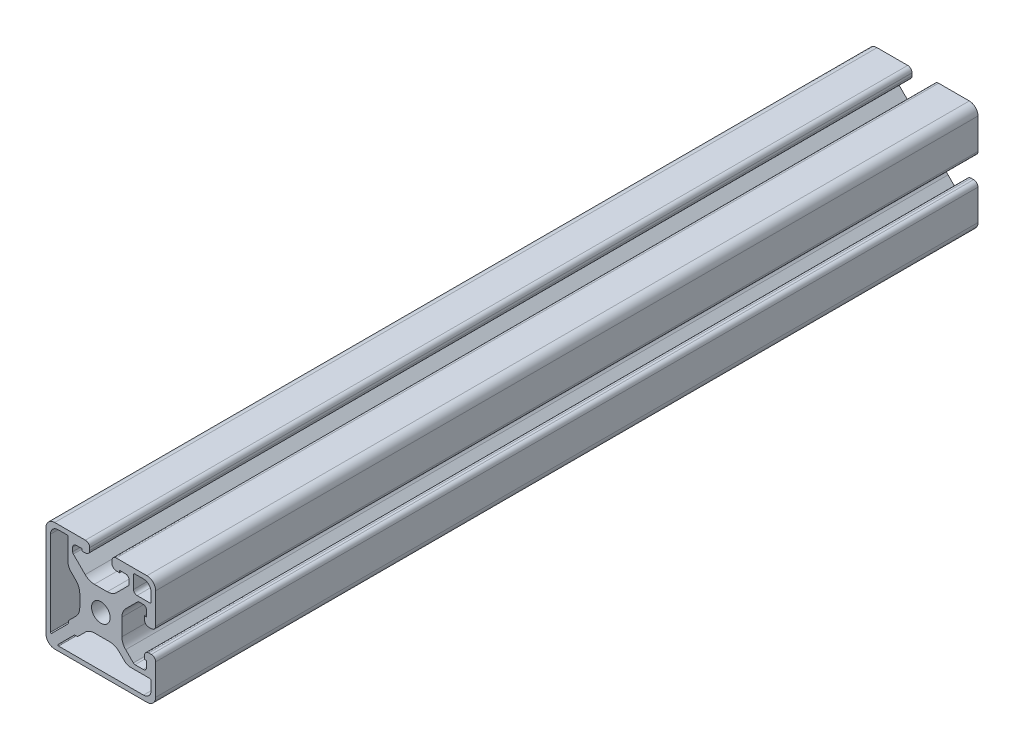
SolidWorks part; units mm, degrees
material "6105-T5 Aluminum"
ref_plane "Front Plane" through (0, 0, 0) normal (0, 0, 1) x (1, 0, 0)
ref_plane "Top Plane" through (0, 0, 0) normal (0, 1, 0) x (1, 0, 0)
ref_plane "Right Plane" through (0, 0, 0) normal (1, 0, 0) x (0, 0, -1)
sketch "Sketch1" plane through (0, 0, 0) normal (0, 0, 1) x (1, 0, 0)
  line L0 (20.9471, 20.9471) -> (-21.7247, -21.7247) construction
  line L1 (-28.5091, 0) -> (25.9724, 0) construction
  line L2 (2.356, 7.7) -> (-2.356, 7.7)
  line L3 (-2.2915, -7.67) -> (3.3048, -7.67)
  line L26 (-9.0762, -5.7416) -> (-11.6227, -8.288)
  line L27 (-7.685, 2.23) -> (-7.685, -2.3829)
  line L28 (-11.0051, 7.5175) -> (-9.0762, 5.5886)
  line L29 (-11.935, 17.954) -> (-11.935, 9.7626)
  line L30 (-15.556, 18.335) -> (-12.316, 18.335)
  line L31 (-18.35, -15.4141) -> (-18.35, 15.541)
  line L32 (-12.069, -9.7356) -> (-17.924, -15.5906)
  line L33 (-11.8458, -9.1968) -> (-11.8458, -8.8268)
  line L34 (-20, 16.825) -> (-20, -16.825)
  line L35 (-16.825, -20) -> (0, -20)
  line L37 (-5.7146, 9.0912) -> (-10.0246, 13.4012)
  line L38 (-10.285, 14.0298) -> (-10.285, 15.4325)
  line L39 (-9.015, 16.7025) -> (-6.8785, 16.7025)
  line L40 (-6.8785, 16.7025) -> (-6.8785, 15.94)
  line L41 (-6.8785, 15.94) -> (-5.6348, 15.94)
  line L42 (-4.06, 17.5148) -> (-4.06, 18.4252)
  line L43 (-5.6348, 20) -> (-13.1857, 20)
  line L44 (-13.1857, 20) -> (-16.825, 20)
  line L46 (-8.2816, -11.6926) -> (-5.6501, -9.0612)
  line L47 (-8.8204, -11.9158) -> (-9.2667, -11.9158)
  line L48 (0, -18.35) -> (-15.4141, -18.35)
  line L49 (-15.5906, -17.924) -> (-9.8056, -12.139)
  line L50 (0, 22.3463) -> (0, -22.9035) construction
  line L62 (18.35, -12.4299) -> (18.35, -15.556)
  line L63 (10.8523, -11.935) -> (17.8551, -11.935)
  line L64 (15.556, -18.35) -> (0, -18.35)
  line L65 (18.35, 15.556) -> (18.35, 12.316)
  line L66 (12.316, 18.35) -> (15.556, 18.35)
  line L67 (11.935, 13.205) -> (11.935, 17.969)
  line L68 (17.969, 11.935) -> (13.205, 11.935)
  line L70 (6.6634, -9.0612) -> (8.6072, -11.0051)
  line L71 (0, -20) -> (16.825, -20)
  line L72 (20, -16.825) -> (20, -13.0495)
  line L73 (20, -13.0495) -> (20, -5.6348)
  line L74 (18.4252, -4.06) -> (17.5148, -4.06)
  line L75 (15.94, -5.6348) -> (15.94, -6.8785)
  line L76 (15.94, -6.8785) -> (16.7025, -6.8785)
  line L77 (16.7025, -6.8785) -> (16.7025, -9.015)
  line L78 (15.4325, -10.285) -> (12.4956, -10.285)
  line L79 (11.867, -10.0246) -> (9.0762, -7.2338)
  line L80 (7.685, -3.8752) -> (7.685, 2.341)
  line L81 (9.0762, 5.6996) -> (13.4012, 10.0246)
  line L82 (14.0298, 10.285) -> (15.432, 10.285)
  line L83 (16.702, 9.015) -> (16.702, 6.8785)
  line L84 (16.702, 6.8785) -> (15.94, 6.8785)
  line L85 (15.94, 6.8785) -> (15.94, 5.6348)
  line L86 (17.5148, 4.06) -> (18.4252, 4.06)
  line L87 (20, 5.6348) -> (20, 12.9805)
  line L88 (20, 12.9805) -> (20, 16.825)
  line L89 (16.825, 20) -> (13.0709, 20)
  line L90 (13.0709, 20) -> (5.6348, 20)
  line L91 (4.06, 18.4252) -> (4.06, 17.5148)
  line L92 (5.6348, 15.94) -> (6.8785, 15.94)
  line L93 (6.8785, 15.94) -> (6.8785, 16.7025)
  line L94 (6.8785, 16.7025) -> (9.015, 16.7025)
  line L95 (10.285, 15.4325) -> (10.285, 14.0298)
  line L96 (10.0246, 13.4012) -> (5.7146, 9.0912)
  arc A19 (-9.0762, -5.7416) -> (-7.685, -2.3829) centre (-12.4348, -2.3829) ccw
  arc A20 (-7.685, 2.23) -> (-9.0762, 5.5886) centre (-12.4348, 2.23) ccw
  arc A21 (-11.935, 9.7626) -> (-11.0051, 7.5175) centre (-8.76, 9.7626) ccw
  arc A22 (-11.935, 17.954) -> (-12.316, 18.335) centre (-12.316, 17.954) ccw
  arc A23 (-15.556, 18.335) -> (-18.35, 15.541) centre (-15.556, 15.541) ccw
  arc A24 (-18.35, -15.4141) -> (-17.924, -15.5906) centre (-18.1005, -15.4141) ccw
  arc A25 (-20, -16.825) -> (-16.825, -20) centre (-16.825, -16.825) ccw
  arc A26 (-5.7146, 9.0912) -> (-2.356, 7.7) centre (-2.356, 12.4498) ccw
  arc A27 (-10.285, 14.0298) -> (-10.0246, 13.4012) centre (-9.396, 14.0298) ccw
  arc A28 (-9.015, 16.7025) -> (-10.285, 15.4325) centre (-9.015, 15.4325) ccw
  arc A29 (-5.6348, 15.94) -> (-4.06, 17.5148) centre (-5.6348, 17.5148) ccw
  arc A30 (-4.06, 18.4252) -> (-5.6348, 20) centre (-5.6348, 18.4252) ccw
  arc A31 (-16.825, 20) -> (-20, 16.825) centre (-16.825, 16.825) ccw
  arc A32 (-12.069, -9.7356) -> (-11.8458, -9.1968) centre (-12.6078, -9.1968) ccw
  arc A33 (-11.6227, -8.288) -> (-11.8458, -8.8268) centre (-11.0838, -8.8268) ccw
  arc A34 (-2.2915, -7.67) -> (-5.6501, -9.0612) centre (-2.2915, -12.4198) ccw
  arc A35 (-8.8204, -11.9158) -> (-8.2816, -11.6926) centre (-8.8204, -11.1538) ccw
  arc A36 (-9.2667, -11.9158) -> (-9.8056, -12.139) centre (-9.2667, -12.6778) ccw
  arc A37 (-15.5906, -17.924) -> (-15.4141, -18.35) centre (-15.4141, -18.1005) ccw
  circle A45 centre (0, 0) radius 3.4
  arc A46 (15.556, -18.35) -> (18.35, -15.556) centre (15.556, -15.556) ccw
  arc A47 (18.35, -12.4299) -> (17.8551, -11.935) centre (17.8551, -12.4299) ccw
  arc A48 (17.969, 11.935) -> (18.35, 12.316) centre (17.969, 12.316) ccw
  arc A49 (18.35, 15.556) -> (15.556, 18.35) centre (15.556, 15.556) ccw
  arc A50 (12.316, 18.35) -> (11.935, 17.969) centre (12.316, 17.969) ccw
  arc A51 (11.935, 13.205) -> (13.205, 11.935) centre (13.205, 13.205) ccw
  arc A52 (6.6634, -9.0612) -> (3.3048, -7.67) centre (3.3048, -12.4198) ccw
  arc A53 (8.6072, -11.0051) -> (10.8523, -11.935) centre (10.8523, -8.76) ccw
  arc A54 (16.825, -20) -> (20, -16.825) centre (16.825, -16.825) ccw
  arc A55 (20, -5.6348) -> (18.4252, -4.06) centre (18.4252, -5.6348) ccw
  arc A56 (17.5148, -4.06) -> (15.94, -5.6348) centre (17.5148, -5.6348) ccw
  arc A57 (15.4325, -10.285) -> (16.7025, -9.015) centre (15.4325, -9.015) ccw
  arc A58 (11.867, -10.0246) -> (12.4956, -10.285) centre (12.4956, -9.396) ccw
  arc A59 (7.685, -3.8752) -> (9.0762, -7.2338) centre (12.4348, -3.8752) ccw
  arc A60 (9.0762, 5.6996) -> (7.685, 2.341) centre (12.4348, 2.341) ccw
  arc A61 (14.0298, 10.285) -> (13.4012, 10.0246) centre (14.0298, 9.396) ccw
  arc A62 (16.702, 9.015) -> (15.432, 10.285) centre (15.432, 9.015) ccw
  arc A63 (15.94, 5.6348) -> (17.5148, 4.06) centre (17.5148, 5.6348) ccw
  arc A64 (18.4252, 4.06) -> (20, 5.6348) centre (18.4252, 5.6348) ccw
  arc A65 (20, 16.825) -> (16.825, 20) centre (16.825, 16.825) ccw
  arc A66 (5.6348, 20) -> (4.06, 18.4252) centre (5.6348, 18.4252) ccw
  arc A67 (4.06, 17.5148) -> (5.6348, 15.94) centre (5.6348, 17.5148) ccw
  arc A68 (10.285, 15.4325) -> (9.015, 16.7025) centre (9.015, 15.4325) ccw
  arc A69 (10.0246, 13.4012) -> (10.285, 14.0298) centre (9.396, 14.0298) ccw
  arc A70 (2.356, 7.7) -> (5.7146, 9.0912) centre (2.356, 12.4498) ccw
  dimension "D11" = 6.8
  dimension "D1" = 45
  dimension "D2" = 15.37
  dimension "D3" = 20.57
  dimension "D4" = 20
  dimension "D5" = 3.3
  dimension "D6" = 4.06
  dimension "D7" = 40
  dimension "D8" = 1.65
  dimension "D9" = 1.65
  dimension "D10" = 15.37
  dimension "D12" = 8.12
  dimension "D13" = 1.65
  dimension "D14" = 12.3
extrude "Extrude1" add sketch "Sketch1" against normal blind 300
